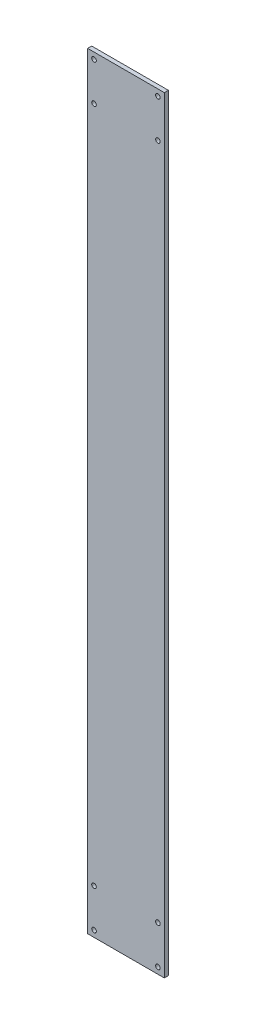
SolidWorks part; units mm, degrees
ref_plane "Front Plane" through (0, 0, 0) normal (0, 0, 1) x (1, 0, 0)
ref_plane "Top Plane" through (0, 0, 0) normal (0, 1, 0) x (1, 0, 0)
ref_plane "Right Plane" through (0, 0, 0) normal (1, 0, 0) x (0, 0, -1)
sketch "Sketch2" plane through (0, 0, 0) normal (0, 0, 1) x (1, 0, 0)
  line L1 (-30, 300) -> (30, 300)
  line L2 (-30, 300) -> (-30, -300)
  line L3 (-30, -300) -> (30, -300)
  line L4 (30, 300) -> (30, -300)
  line L5 (-30, 300) -> (30, -300) construction
  line L6 (-30, -300) -> (30, 300) construction
  point P0 (0, 0)
  dimension "D1" = 60
  dimension "D2" = 600
extrude "Boss-Extrude1" add sketch "Sketch2" along normal blind 3.175
hole_wizard "M3 Clearance Hole1" positions "Sketch5" profile "Sketch6" hole size "M3" standard "ANSI Metric"
sketch "Sketch5" plane through (0, 0, 3.175) normal (0, 0, 1) x (1, 0, 0)
  line L1 (-25, -265) -> (25, -265)
  line L2 (-25, -265) -> (-25, -295)
  line L3 (-25, -295) -> (25, -295)
  line L4 (25, -265) -> (25, -295)
  line L5 (-25, -265) -> (25, -295) construction
  line L6 (-25, -295) -> (25, -265) construction
  line L7 (0, 0) -> (50000, 0) construction
  line L8 (-30, -300) -> (30, -300) construction
  point P2 (25, -295)
  point P33 (-25, -265)
  point P34 (-25, -295)
  point P35 (25, -265)
  point P41 (0, -265)
  point P53 (-25, 265)
  point P54 (-25, 295)
  point P55 (25, 295)
  point P56 (25, 265)
  dimension "D1" = 50
  dimension "D2" = 30
  dimension "D3" = 5
sketch "Sketch6" plane through (25, -295, 3.175) normal (1, 0, 0) x (0, -1, 0)
  line L0 (0, 0) -> (0, 5)
  line L1 (0, 5) -> (1.8, 3.9185)
  line L2 (1.8, 3.9185) -> (1.8, 0)
  line L5 (1.8, 0) -> (0, 0)
  line L10 (0, 5) -> (-1.8, 3.9185) construction
  line L11 (0, -6.35) -> (0, 107.95) construction
  dimension "Hole Dia." = 3.6
  dimension "Hole Depth" = 5
  dimension "Drill Angle" = 118
